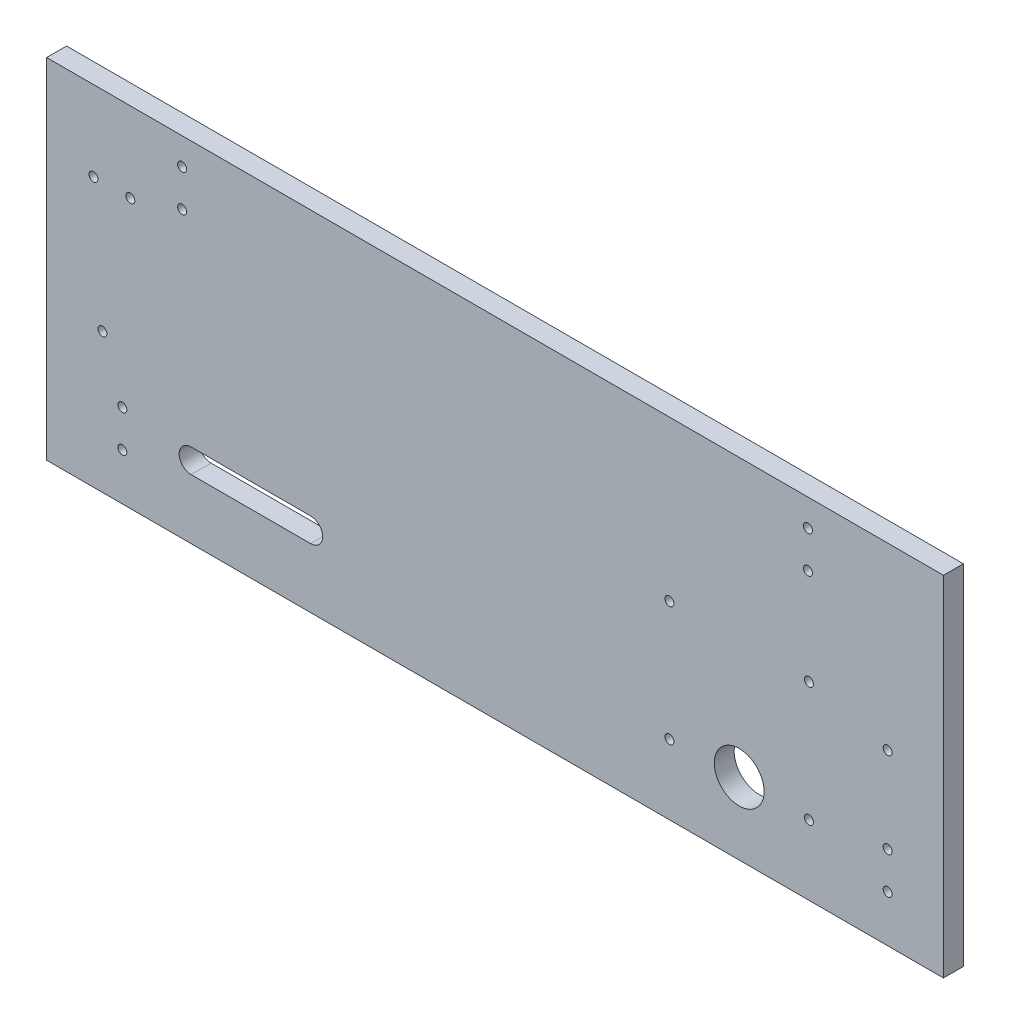
SolidWorks part; units mm, degrees
material "Multistrato di pioppo"
ref_plane "Piano frontale" through (0, 0, 0) normal (0, 0, 1) x (1, 0, 0)
ref_plane "Piano superiore" through (0, 0, 0) normal (0, 1, 0) x (1, 0, 0)
ref_plane "Piano destro" through (0, 0, 0) normal (1, 0, 0) x (0, 0, -1)
sketch "Schizzo1" plane through (0, 0, 0) normal (0, 0, 1) x (1, 0, 0)
  line L1 (0, 0) -> (450, 0)
  line L2 (0, 0) -> (0, 175)
  line L3 (0, 175) -> (450, 175)
  line L4 (450, 0) -> (450, 175)
  dimension "D1" = 450
  dimension "D2" = 175
extrude "Estrusione-Estrusione1" add sketch "Schizzo1" along normal blind 10
sketch "Schizzo2" plane through (0, 0, 10) normal (0, 0, 1) x (1, 0, 0)
  line L0 (102.5, 36) -> (347.5, 36) construction
  line L1 (225, 0) -> (225, 36) construction
  line L2 (0, 0) -> (450, 0) construction
  line L3 (72.5, 36) -> (132.5, 36) construction
  line L4 (72.5, 42) -> (132.5, 42)
  line L5 (72.5, 30) -> (132.5, 30)
  circle A1 centre (347.5, 36) radius 12.5
  arc A2 (72.5, 42) -> (72.5, 30) centre (72.5, 36) ccw
  arc A3 (132.5, 30) -> (132.5, 42) centre (132.5, 36) ccw
  circle A8 centre (382, 161.5) radius 2.25
  circle A9 centre (382, 143) radius 2.25
  circle A10 centre (68, 161.5) radius 2.25
  circle A11 centre (68, 143) radius 2.25
  circle A12 centre (38, 42) radius 2.25
  circle A13 centre (38, 23.5) radius 2.25
  circle A14 centre (422, 23.5) radius 2.25
  circle A15 centre (422, 42) radius 2.25
  circle A16 centre (23.5, 134.9337) radius 2.25
  circle A17 centre (42, 134.9337) radius 2.25
  circle A18 centre (28, 70) radius 2.25
  circle A19 centre (422, 85) radius 2.25
  circle A20 centre (312.5, 95) radius 2.25
  circle A21 centre (382.5, 95) radius 2.25
  circle A22 centre (382.5, 35) radius 2.25
  circle A23 centre (312.5, 35) radius 2.25
  point P9 (102.5, 36)
  dimension "D2" = 25
  dimension "D3" = 12
  dimension "D5" = 60
  dimension "D6" = 4.5
  dimension "D20" = 4.5
  dimension "D11" = 4.5
  dimension "D1" = 36
  dimension "D4" = 245
extrude "Taglio-Estrusione1" cut sketch "Schizzo2" against normal blind 10
